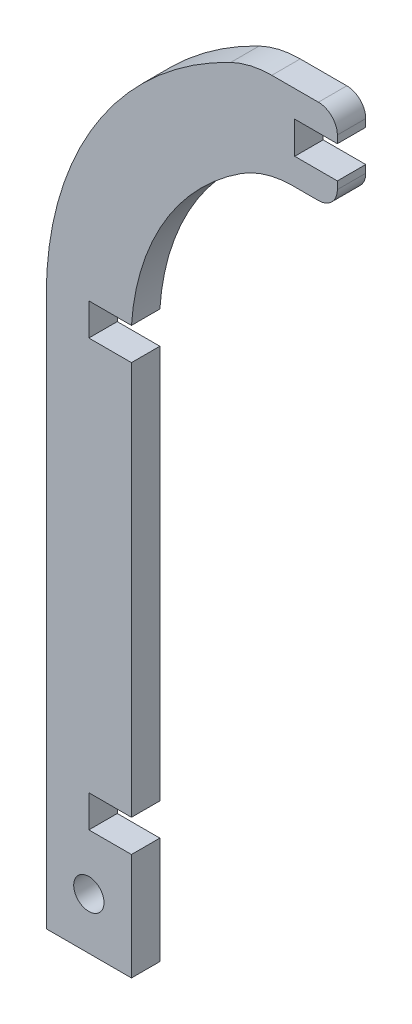
SolidWorks part; units mm, degrees
material "Thornel Mat VMA"
ref_plane "Front Plane" through (0, 0, 0) normal (0, 0, 1) x (1, 0, 0)
ref_plane "Top Plane" through (0, 0, 0) normal (0, 1, 0) x (1, 0, 0)
ref_plane "Right Plane" through (0, 0, 0) normal (1, 0, 0) x (0, 0, -1)
sketch "Sketch1" plane through (0, 0, 0) normal (0, 0, 1) x (1, 0, 0)
  line L0 (-54.5, 0) -> (-45.5, 0)
  line L1 (-45.5, 0) -> (-45.5, 11.3)
  line L2 (-54.5, 0) -> (-54.5, 58)
  line L3 (-45.5, 11.3) -> (-50, 11.3)
  line L4 (-50, 11.3) -> (-50, 14.7)
  line L5 (-50, 14.7) -> (-45.5, 14.7)
  line L6 (-45.5, 14.7) -> (-45.5, 56.3)
  line L7 (-45.5, 56.3) -> (-50, 56.3)
  line L8 (-50, 56.3) -> (-50, 59.7)
  line L9 (-50, 59.7) -> (-45.5, 59.7)
  line L10 (50, 0) -> (-50, 0) construction
  line L11 (0, 0) -> (0, 13) construction
  line L12 (0, 13) -> (0, 58) construction
  line L13 (0, 58) -> (0, 85.5) construction
  line L14 (50, 58) -> (-50, 58) construction
  line L15 (50, 13) -> (-50, 13) construction
  line L16 (28.25, 85.5) -> (-28.25, 85.5) construction
  line L17 (-28.25, 83.8) -> (-28.25, 87.2)
  line L18 (-28.25, 87.2) -> (-23.75, 87.2)
  line L19 (-23.75, 87.2) -> (-23.75, 90)
  line L20 (-23.75, 90) -> (-30.6727, 90)
  line L21 (-28.25, 83.8) -> (-23.75, 83.8)
  line L22 (-23.75, 83.8) -> (-23.75, 81)
  line L23 (-23.75, 81) -> (-28.4743, 81)
  circle A0 centre (-20.0848, 58) radius 34.4152 construction
  circle A1 centre (-30.6727, 80) radius 10 construction
  arc A2 (-54.5, 58) -> (-35.0093, 89.0108) centre (-20.0848, 58) cw
  arc A3 (-35.0093, 89.0108) -> (-30.6727, 90) centre (-30.6727, 80) cw
  circle A4 centre (-28.4743, 71) radius 10 construction
  circle A5 centre (-20.0848, 58) radius 25.472 construction
  arc A6 (-45.5, 59.7) -> (-33.8966, 79.4023) centre (-20.0848, 58) cw
  arc A7 (-33.8966, 79.4023) -> (-28.4743, 81) centre (-28.4743, 71) cw
  point P3 (-50, 13)
  point P4 (-50, 0)
  point P5 (-50, 58)
  point P11 (-50, 5.4375)
  point P22 (0, 0)
  point P26 (0, 58)
  point P29 (0, 13)
  point P32 (0, 85.5)
  point P35 (-28.25, 85.5)
  point P49 (-45.5, 8.8467)
  dimension "D10" = 68.8305
  dimension "D11" = 20
  dimension "D12" = 20
  dimension "D1" = 9
  dimension "D2" = 5.4375
  dimension "D3" = 3.4
  dimension "D4" = 13
  dimension "D5" = 100
  dimension "D6" = 45
  dimension "D7" = 27.5
  dimension "D8" = 56.5
  dimension "D9" = 2.8
extrude "Boss-Extrude1" add sketch "Sketch1" along normal mid plane 3
hole_wizard "M3 Clearance Hole1" positions "Sketch2" profile "Sketch3" hole size "M3" standard "ANSI Metric"
sketch "Sketch2" plane through (0, 0, 1.5) normal (0, 0, 1) x (1, 0, 0)
  point P0 (-50, 5.4375)
sketch "Sketch3" plane through (-50, 5.4375, 1.5) normal (1, 0, 0) x (0, -1, 0)
  line L0 (0, 0) -> (0, 10.9614)
  line L1 (0, 10.9614) -> (1.6, 10)
  line L2 (1.6, 10) -> (1.6, 0)
  line L5 (1.6, 0) -> (0, 0)
  line L10 (0, 10.9614) -> (-1.6, 10) construction
  line L11 (0, -6.35) -> (0, 107.95) construction
  dimension "Hole Dia." = 3.2
  dimension "Hole Depth" = 10
  dimension "Drill Angle" = 118
fillet "Fillet1" radius 2 2 edges at (-23.75, 90, 0) (-23.75, 81, 0)
